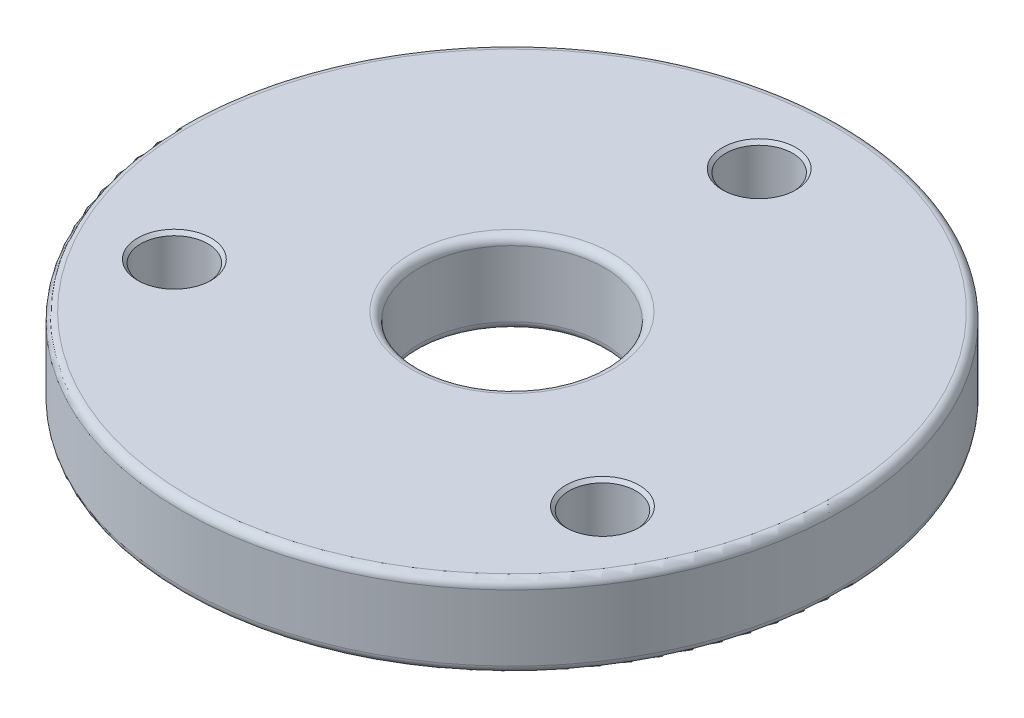
SolidWorks part; units mm, degrees
ref_plane "Front Plane" through (0, 0, 0) normal (0, 0, 1) x (1, 0, 0)
ref_plane "Top Plane" through (0, 0, 0) normal (0, 1, 0) x (1, 0, 0)
ref_plane "Right Plane" through (0, 0, 0) normal (1, 0, 0) x (0, 0, -1)
sketch "Sketch1" plane through (0, 0, 0) normal (0, 1, 0) x (1, 0, 0)
  circle A0 centre (0, 0) radius 100
  circle A1 centre (0, 0) radius 75 construction
  circle A2 centre (0, 0) radius 28
  circle A3 centre (0, 75) radius 10.15
  circle A4 centre (64.9519, -37.5) radius 10.15
  circle A5 centre (-64.9519, -37.5) radius 10.15
  point P13 (0, 0)
  dimension "D1" = 200
  dimension "D2" = 150
  dimension "D3" = 56
  dimension "D4" = 20.3
  dimension "D5" = 3
extrude "Boss-Extrude1" add sketch "Sketch1" along normal mid plane 25
fillet "Fillet1" radius 2.5 4 edges at (0, -12.5, 28) (0, 12.5, 28) (0, -12.5, 100) (0, 12.5, 100)
chamfer "Chamfer1" distance 1 angle 45 6 edges at (64.9519, -12.5, 47.65) (64.9519, 12.5, 47.65) (0, -12.5, -64.85) (0, 12.5, -64.85) (-64.9519, -12.5, 47.65) (-64.9519, 12.5, 47.65)
